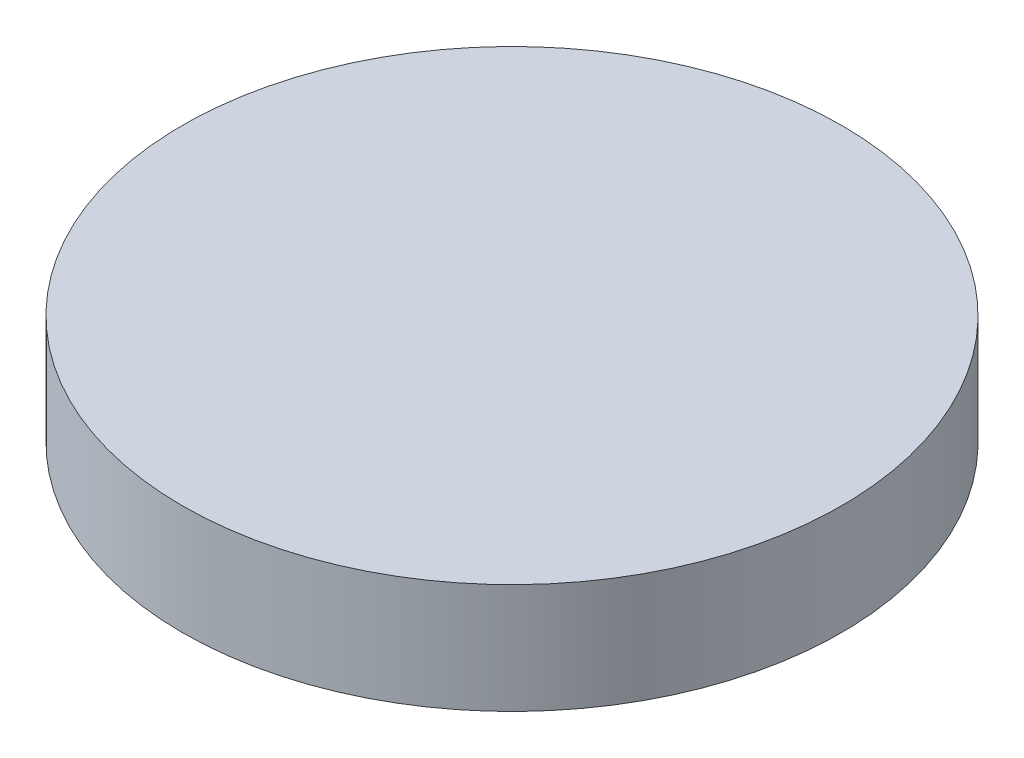
SolidWorks part; units mm, degrees
ref_plane "Front Plane" through (0, 0, 0) normal (0, 0, 1) x (1, 0, 0)
ref_plane "Top Plane" through (0, 0, 0) normal (0, 1, 0) x (1, 0, 0)
ref_plane "Right Plane" through (0, 0, 0) normal (1, 0, 0) x (0, 0, -1)
sketch "Sketch1" plane through (0, 0, 0) normal (0, 1, 0) x (1, 0, 0)
  circle A0 centre (0, 0) radius 19.05
  dimension "D1" = 38.1
extrude "Boss-Extrude1" add sketch "Sketch1" along normal blind 6.35
sketch "Sketch2" plane through (0, 0, 0) normal (0, -1, 0) x (1, 0, 0)
  circle A0 centre (0, 0) radius 17.653
  dimension "D1" = 35.306
extrude "Cut-Extrude1" cut sketch "Sketch2" against normal blind 2.8702
